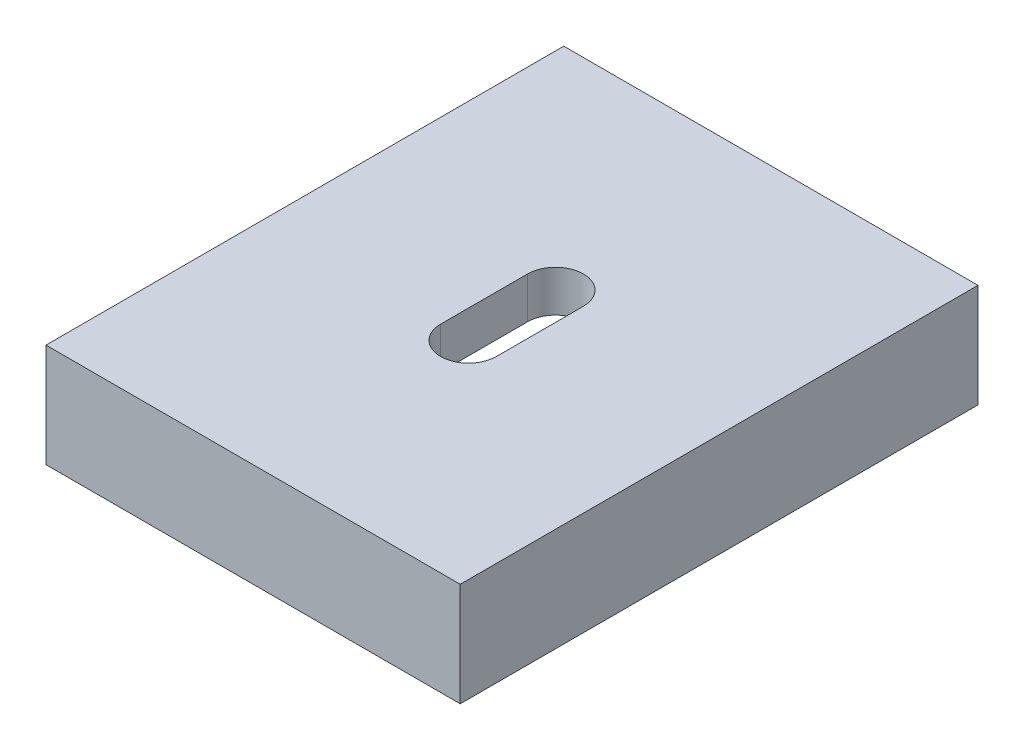
SolidWorks part; units mm, degrees
ref_plane "前视基准面" through (0, 0, 0) normal (0, 0, 1) x (1, 0, 0)
ref_plane "上视基准面" through (0, 0, 0) normal (0, 1, 0) x (1, 0, 0)
ref_plane "右视基准面" through (0, 0, 0) normal (1, 0, 0) x (0, 0, -1)
sketch "草图1" plane through (0, 0, 0) normal (0, 1, 0) x (0, 0, -1)
  line L0 (0, 20) -> (0, -20) construction
  line L1 (-25, 20) -> (25, 20)
  line L2 (-25, 20) -> (-25, -20)
  line L3 (-25, -20) -> (25, -20)
  line L4 (25, 20) -> (25, -20)
  dimension "D1" = 50
  dimension "D2" = 40
extrude "凸台-拉伸1" add sketch "草图1" along normal blind 10
sketch "草图7" plane through (0, 10, 0) normal (0, 1, 0) x (0, 0, -1)
  line L0 (25, 20) -> (-25, 20) construction
  line L1 (-20.5, -13) -> (20.5, -13)
  line L2 (-20.5, -13) -> (-20.5, 13)
  line L3 (-20.5, 13) -> (20.5, 13)
  line L4 (20.5, -13) -> (20.5, 13)
  line L5 (-20.5, -13) -> (20.5, 13) construction
  line L6 (-20.5, 13) -> (20.5, -13) construction
  line L9 (-25, 20) -> (-25, -20) construction
  point P0 (0, 0)
  dimension "D1" = 4.5
  dimension "D2" = 7
extrude "切除-拉伸2" cut sketch "草图7" along normal blind 6 from surface at -10 starting at face at (0, 0, 0)
sketch "草图8" plane through (0, 6, 0) normal (0, -1, 0) x (0, 0, 1)
  line L0 (0, -2.7) -> (0, 2.7) construction
  line L1 (-4.2, 2.7) -> (4.2, 2.7)
  line L2 (-4.2, 2.7) -> (-4.2, -2.7)
  line L3 (-4.2, -2.7) -> (4.2, -2.7)
  line L4 (4.2, 2.7) -> (4.2, -2.7)
  line L5 (-4.2, 2.7) -> (4.2, -2.7) construction
  line L6 (-4.2, -2.7) -> (4.2, 2.7) construction
  circle A0 centre (4.2, 0) radius 2.7
  circle A1 centre (-4.2, 0) radius 2.7
  point P0 (0, 0)
  dimension "D1" = 5.4
  dimension "D2" = 8.4
extrude "切除-拉伸3" cut sketch "草图8" against normal through all contours A1 L2 | A1 L2 | L1 A1 L3 A0 | L4 A0 | L4 A0
